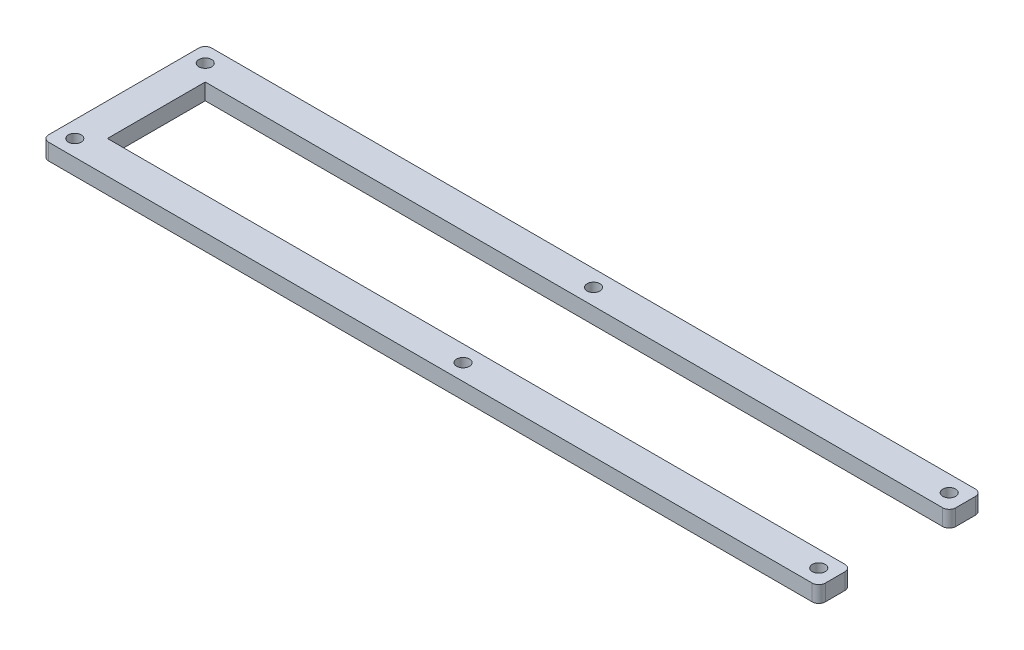
SolidWorks part; units mm, degrees
ref_plane "Front Plane" through (0, 0, 0) normal (0, 0, 1) x (1, 0, 0)
ref_plane "Top Plane" through (0, 0, 0) normal (0, 1, 0) x (1, 0, 0)
ref_plane "Right Plane" through (0, 0, 0) normal (1, 0, 0) x (0, 0, -1)
sketch "Sketch1" plane through (0, 0, 0) normal (0, 1, 0) x (1, 0, 0)
  line L1 (-144.845, 19.05) -> (144.845, 19.05)
  line L2 (-144.845, 19.05) -> (-144.845, -19.05)
  line L3 (-144.845, -19.05) -> (144.845, -19.05)
  line L4 (144.845, 19.05) -> (144.845, -19.05)
  line L5 (-144.845, 19.05) -> (144.845, -19.05) construction
  line L6 (-144.845, -19.05) -> (144.845, 19.05) construction
  line L7 (144.845, -19.05) -> (144.845, -31.75)
  line L8 (-144.845, 19.05) -> (144.845, 19.05)
  line L9 (-144.845, 19.05) -> (-144.845, 31.75)
  line L10 (-144.845, 31.75) -> (144.845, 31.75)
  line L11 (144.845, 19.05) -> (144.845, 31.75)
  line L12 (-144.845, -19.05) -> (144.845, -19.05)
  line L13 (-144.845, -19.05) -> (-144.845, -31.75)
  line L14 (-144.845, -31.75) -> (144.845, -31.75)
  line L15 (144.845, -19.05) -> (144.845, -31.75)
  line L16 (-144.845, 31.75) -> (-157.545, 31.75)
  line L17 (-144.845, 31.75) -> (-144.845, -31.75)
  line L18 (-144.845, -31.75) -> (-157.545, -31.75)
  line L19 (-157.545, 31.75) -> (-157.545, -31.75)
  line L20 (144.845, 31.75) -> (144.845, 19.05)
  circle A0 centre (-151.195, 25.4) radius 2.49
  circle A2 centre (-151.195, -25.4) radius 2.49
  circle A3 centre (0, 25.4) radius 2.49
  circle A4 centre (0, -25.4) radius 2.49
  circle A5 centre (138.495, 25.4) radius 2.49
  circle A6 centre (138.495, -25.4) radius 2.49
  point P0 (0, 0)
  point P26 (-151.195, 25.4)
  point P27 (0, 0)
  dimension "D7" = 6.35
  dimension "D8" = 6.35
  dimension "D9" = 4.98
  dimension "D10" = 4.98
  dimension "D11" = 4.98
  dimension "D12" = 6.35
  dimension "D13" = 4.98
  dimension "D14" = 4.98
  dimension "D15" = 4.98
  dimension "D16" = 6.35
  dimension "D18" = 6.35
  dimension "D19" = 144.845
  dimension "D21" = 144.845
  dimension "D24" = 6.35
  dimension "D3" = 6.35
  dimension "D1" = 289.69
  dimension "D2" = 38.1
  dimension "D4" = 12.7
  dimension "D5" = 12.7
  dimension "D6" = 12.7
  dimension "D17" = 6.35
  dimension "D20" = 6.35
  dimension "D22" = 6.35
  dimension "D23" = 289.69
  dimension "D25" = 6.35
extrude "Boss-Extrude1" add sketch "Sketch1" along normal blind 6.35 contours L13 L14 L7 L3 A6 A4 | L16 L19 L18 L13 L2 L9 A2 A0 | L1 L11 L10 L9 A5 A3
fillet "Fillet1" radius 2.54 6 edges at (144.845, 3.175, -31.75) (-157.545, 3.175, -31.75) (-157.545, 3.175, 31.75) (144.845, 3.175, -19.05) (144.845, 3.175, 19.05) (144.845, 3.175, 31.75)
